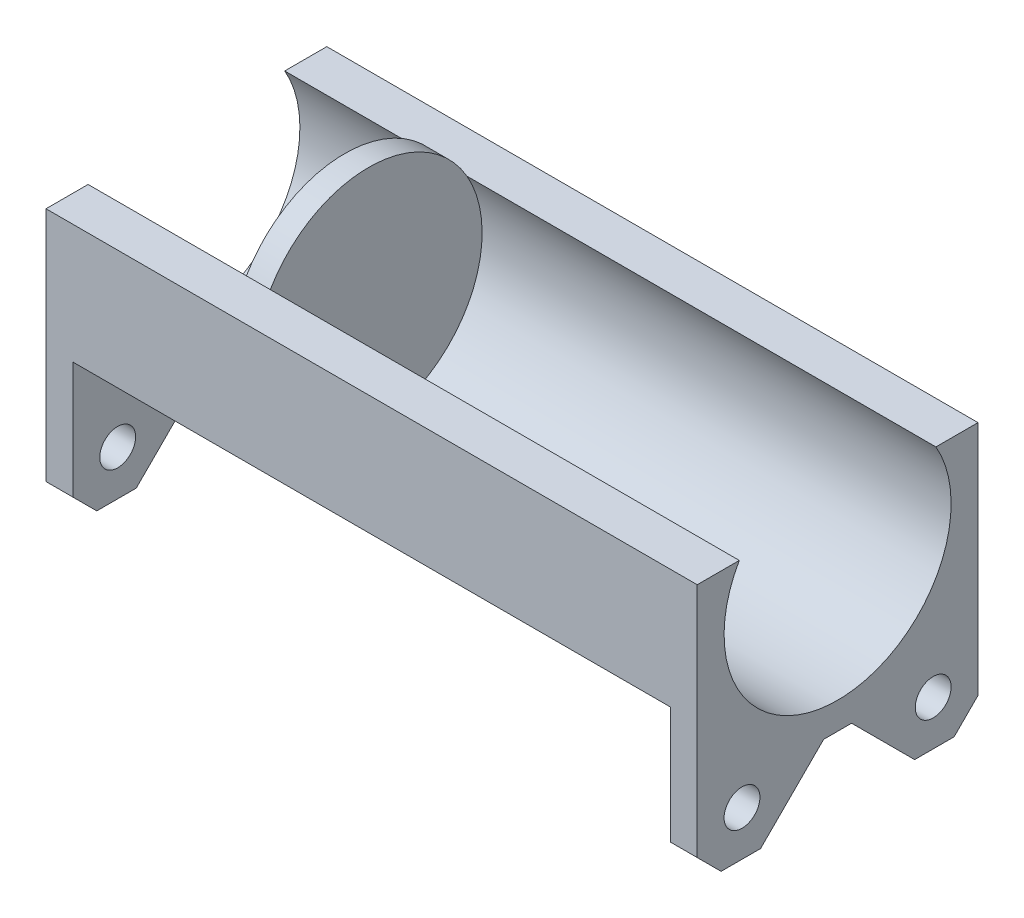
SolidWorks part; units mm, degrees
ref_plane "Front Plane" through (0, 0, 0) normal (0, 0, 1) x (1, 0, 0)
ref_plane "Top Plane" through (0, 0, 0) normal (0, 1, 0) x (1, 0, 0)
ref_plane "Right Plane" through (0, 0, 0) normal (1, 0, 0) x (0, 0, -1)
sketch "Sketch1" plane through (0, 0, 0) normal (0, 0, 1) x (1, 0, 0)
  line L0 (51, 0) -> (-51, 0)
  line L1 (-30, 0) -> (-30, 37)
  line L2 (-55, 0) -> (55, 0)
  line L3 (-55, 0) -> (-55, -20)
  line L4 (55, 0) -> (55, -20)
  point P3 (0, 0)
  point P6 (0, 0)
  point P9 (0, 0)
  dimension "D1" = 102
  dimension "D2" = 81
  dimension "D3" = 110
  dimension "D4" = 37
  dimension "D5" = 20
sketch "Sketch4" plane through (0, 0, 0) normal (1, 0, 0) x (0, 0, -1)
  circle A0 centre (0, 0) radius 19
  dimension "D1" = 38
extrude "Boss-Extrude1" add sketch "Sketch4" against normal blind 4 from offset 24 offset against normal yes
sketch "Sketch5" plane through (0, 0, 0) normal (1, 0, 0) x (0, 0, -1)
  line L0 (0, 0) -> (26.3066, 0) construction
  line L1 (16.4545, 9.5) -> (23.5, 9.5)
  line L2 (23.5, 0) -> (23.5, -26.5518) construction
  line L3 (20.6188, -26.5518) -> (18.3094, -22.5518) construction
  line L4 (18.3094, -22.5518) -> (13.6906, -22.5518) construction
  line L5 (13.6906, -22.5518) -> (11.3812, -26.5518) construction
  line L6 (11.3812, -26.5518) -> (13.6906, -30.5518) construction
  line L7 (13.6906, -30.5518) -> (18.3094, -30.5518) construction
  line L8 (18.3094, -30.5518) -> (20.6188, -26.5518) construction
  line L9 (23.5, 9.5) -> (23.5, -34.0518)
  line L10 (23.5, -34.0518) -> (12.8934, -34.0518)
  line L11 (12.8934, -34.0518) -> (2.3416, -23.5)
  line L12 (2.3416, -23.5) -> (-2.3416, -23.5)
  line L13 (0, 2.2) -> (0, -2.2) construction
  line L14 (-12.8934, -34.0518) -> (-2.3416, -23.5)
  line L15 (-23.5, -34.0518) -> (-12.8934, -34.0518)
  line L16 (-23.5, 9.5) -> (-23.5, -34.0518)
  line L17 (-16.4545, 9.5) -> (-23.5, 9.5)
  arc A0 (-16.4545, 9.5) -> (16.4545, 9.5) centre (0, 0) ccw
  circle A1 centre (0, 0) radius 19 construction
  circle A2 centre (0, 0) radius 23.5 construction
  circle A3 centre (16, -26.5518) radius 7.5 construction
  circle A4 centre (16, -26.5518) radius 4 construction
  circle A5 centre (16, -26.5518) radius 3
  circle A6 centre (-16, -26.5518) radius 3
  point P28 (0, -23.5)
  dimension "D1" = 30
  dimension "D3" = 47
  dimension "D4" = 15
  dimension "D5" = 45
  dimension "D2" = 6
extrude "Boss-Extrude2" add sketch "Sketch5" along normal mid plane 109
sketch "Sketch6" plane through (0, 0, 0) normal (1, 0, 0) x (0, 0, -1)
  line L0 (2.3416, -23.5) -> (7.9691, -23.5)
  line L1 (7.9691, -23.5) -> (23.5, -10.468)
  line L2 (23.5, -34.0518) -> (23.5, 9.5) construction
  line L3 (12.8934, -34.0518) -> (23.5, -34.0518) construction
  line L4 (2.3416, -23.5) -> (-2.3416, -23.5)
  line L5 (0, 29.1785) -> (0, -29.1785) construction
  line L6 (-7.9691, -23.5) -> (-23.5, -10.468)
  line L7 (-2.3416, -23.5) -> (-7.9691, -23.5)
  line L8 (-23.5, -10.468) -> (-23.5, -34.0518)
  line L9 (-23.5, -34.0518) -> (23.5, -34.0518)
  line L10 (23.5, -34.0518) -> (23.5, -10.468)
  circle A0 centre (16, -26.5518) radius 7.5 construction
  dimension "D1" = 40
extrude "Cut-Extrude1" cut sketch "Sketch6" against normal mid plane 100
chamfer "Chamfer1" distance 4 angle 45 4 edges at (52.25, -34.0518, -23.5) (52.25, -34.0518, 23.5) (-52.25, -34.0518, 23.5) (-52.25, -34.0518, -23.5)
